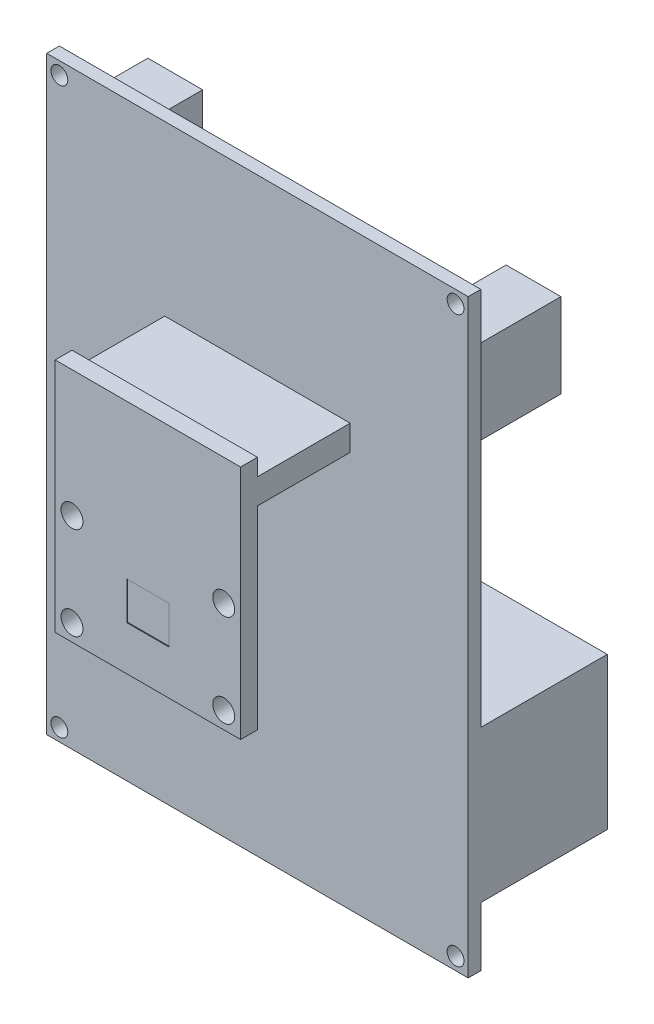
SolidWorks part; units mm, degrees
ref_plane "前视基准面" through (0, 0, 0) normal (0, 0, 1) x (1, 0, 0)
ref_plane "上视基准面" through (0, 0, 0) normal (0, 1, 0) x (1, 0, 0)
ref_plane "右视基准面" through (0, 0, 0) normal (1, 0, 0) x (0, 0, -1)
sketch "草图1" plane through (0, 0, 0) normal (0, 0, 1) x (1, 0, 0)
  line L1 (-25, -35) -> (25, -35)
  line L2 (-25, -35) -> (-25, 35)
  line L3 (-25, 35) -> (25, 35)
  line L4 (25, -35) -> (25, 35)
  line L5 (-25, -35) -> (25, 35) construction
  line L6 (-25, 35) -> (25, -35) construction
  point P0 (0, 0)
extrude "凸台-拉伸1" add sketch "草图1" against normal blind 1.5
sketch "草图2" plane through (0, 0, 0) normal (0, 0, 1) x (1, 0, 0)
  line L0 (-25, 35) -> (-23.5, 35) construction
  line L1 (25, 35) -> (-25, 35) construction
  line L2 (-23.5, 35) -> (-23.5, 33.5) construction
  line L3 (0, 0) -> (0, 20) construction
  line L4 (0, 0) -> (10, 0) construction
  circle A0 centre (-23.5, 33.5) radius 1
  circle A1 centre (23.5, 33.5) radius 1
  circle A2 centre (23.5, -33.5) radius 1
  circle A3 centre (-23.5, -33.5) radius 1
extrude "切除-拉伸1" cut sketch "草图2" against normal blind 1.5
sketch "草图3" plane through (0, 0, -1.5) normal (0, 0, -1) x (-1, 0, 0)
  line L0 (-25, -35) -> (-25, -28) construction
  line L1 (-25, -35) -> (-25, 35) construction
  line L2 (-25, -28) -> (-25, -10)
  line L3 (-25, -10) -> (25, -10)
  line L4 (25, 35) -> (25, -35) construction
  line L5 (25, -10) -> (25, -28)
  line L6 (25, -28) -> (-25, -28)
extrude "凸台-拉伸2" add sketch "草图3" along normal blind 15
sketch "草图4" plane through (0, 0, -1.5) normal (0, 0, -1) x (-1, 0, 0)
  line L2 (-8, -2) -> (0, -2)
  line L3 (0, -2) -> (8, -2)
  line L4 (8, -2) -> (8, 12)
  line L5 (8, 12) -> (-8, 12)
  line L6 (-8, 12) -> (-8, -2)
extrude "凸台-拉伸3" add sketch "草图4" along normal blind 15
sketch "草图5" plane through (0, 0, -1.5) normal (0, 0, -1) x (-1, 0, 0)
  line L0 (-25, 35) -> (-25, 29) construction
  line L1 (-25, -10) -> (-25, 35) construction
  line L2 (-25, 29) -> (-18, 29)
  line L3 (-18, 29) -> (-18, 19)
  line L4 (-18, 19) -> (-25, 19)
  line L5 (-25, 19) -> (-25, 29)
  line L6 (0, 0) -> (0, 15) construction
  line L7 (25, 19) -> (25, 29)
  line L8 (18, 19) -> (25, 19)
  line L9 (18, 29) -> (18, 19)
  line L10 (25, 29) -> (18, 29)
extrude "凸台-拉伸4" add sketch "草图5" along normal blind 10
sketch "草图6" plane through (0, 0, 0) normal (0, 0, 1) x (1, 0, 0)
  line L0 (0, 35) -> (0, 17) construction
  line L1 (25, 35) -> (-25, 35) construction
  line L2 (0, 17) -> (11, 17)
  line L3 (11, 17) -> (11, -11)
  line L4 (11, -11) -> (-11, -11)
  line L5 (-11, -11) -> (-11, 17)
  line L6 (-11, 17) -> (0, 17)
extrude "凸台-拉伸5" add sketch "草图6" along normal blind 13
sketch "草图7" plane through (0, -11, 0) normal (0, -1, 0) x (-1, 0, 0)
  line L0 (11, 0) -> (11, -11)
  line L1 (11, -13) -> (11, 0) construction
  line L2 (11, -11) -> (-11, -11)
  line L3 (-11, -13) -> (-11, 0) construction
  line L4 (-11, -11) -> (-11, 0)
  line L5 (-11, 0) -> (11, 0)
extrude "切除-拉伸2" cut sketch "草图7" against normal blind 23
sketch "草图8" plane through (0, 17, 0) normal (0, 1, 0) x (1, 0, 0)
  line L0 (0, 0) -> (11, 0)
  line L1 (11, 0) -> (11, -11)
  line L2 (11, -13) -> (11, 0) construction
  line L3 (11, -11) -> (-11, -11)
  line L4 (-11, -13) -> (-11, 0) construction
  line L5 (-11, -11) -> (-11, 0)
  line L6 (-11, 0) -> (0, 0)
extrude "切除-拉伸3" cut sketch "草图8" against normal blind 2
sketch "草图9" plane through (-25, 0, 0) normal (-1, 0, 0) x (0, 0, 1)
  line L1 (-11.5, 29) -> (-1.5, 29)
  line L2 (-11.5, 29) -> (-11.5, 19)
  line L3 (-11.5, 19) -> (-1.5, 19)
  line L4 (-1.5, 29) -> (-1.5, 19)
  line L5 (-6.5, 19) -> (-6.5, 29) construction
  line L6 (-11.5, 24) -> (-1.5, 24) construction
  point P200 (-6.5, 24)
extrude "切除-拉伸4" cut sketch "草图9" against normal blind 0.5
sketch "草图10" plane through (25, 0, 0) normal (1, 0, 0) x (0, 0, -1)
  line L1 (1.5, 29) -> (11.5, 29)
  line L2 (1.5, 29) -> (1.5, 19)
  line L3 (1.5, 19) -> (11.5, 19)
  line L4 (11.5, 29) -> (11.5, 19)
  line L5 (6.5, 19) -> (6.5, 29) construction
  line L6 (1.5, 24) -> (11.5, 24) construction
  point P72 (6.5, 24)
extrude "切除-拉伸5" cut sketch "草图10" against normal blind 0.5
sketch "草图11" plane through (0, 0, 13) normal (0, 0, 1) x (1, 0, 0)
  line L0 (-11, -11) -> (-11, -9) construction
  line L1 (-11, 17) -> (-11, -11) construction
  line L2 (-11, -9) -> (-9, -9) construction
  line L4 (-9, -9) -> (9, -9) construction
  line L5 (-9, -9) -> (-9, 2) construction
  line L6 (-9, 2) -> (9, 2) construction
  line L7 (9, -9) -> (9, 2) construction
  line L8 (0, 2) -> (0, -9) construction
  line L9 (-9, -3.5) -> (9, -3.5) construction
  circle A0 centre (-9, 2) radius 1.3
  circle A1 centre (-9, -9) radius 1.3
  circle A2 centre (9, 2) radius 1.3
  circle A3 centre (9, -9) radius 1.3
  point P65 (0, -3.5)
extrude "切除-拉伸6" cut sketch "草图11" against normal up to next
sketch "草图12" plane through (0, 0, 13) normal (0, 0, 1) x (1, 0, 0)
  line L0 (-9, -9) -> (-9, -3.5) construction
  line L1 (-9, -3.5) -> (0, -3.5) construction
  line L3 (-2.5, -1.25) -> (2.5, -1.25)
  line L4 (-2.5, -1.25) -> (-2.5, -5.75)
  line L5 (-2.5, -5.75) -> (2.5, -5.75)
  line L6 (2.5, -1.25) -> (2.5, -5.75)
  line L7 (-2.5, -1.25) -> (2.5, -5.75) construction
  line L8 (-2.5, -5.75) -> (2.5, -1.25) construction
extrude "切除-拉伸8" cut sketch "草图12" against normal blind 0.1
